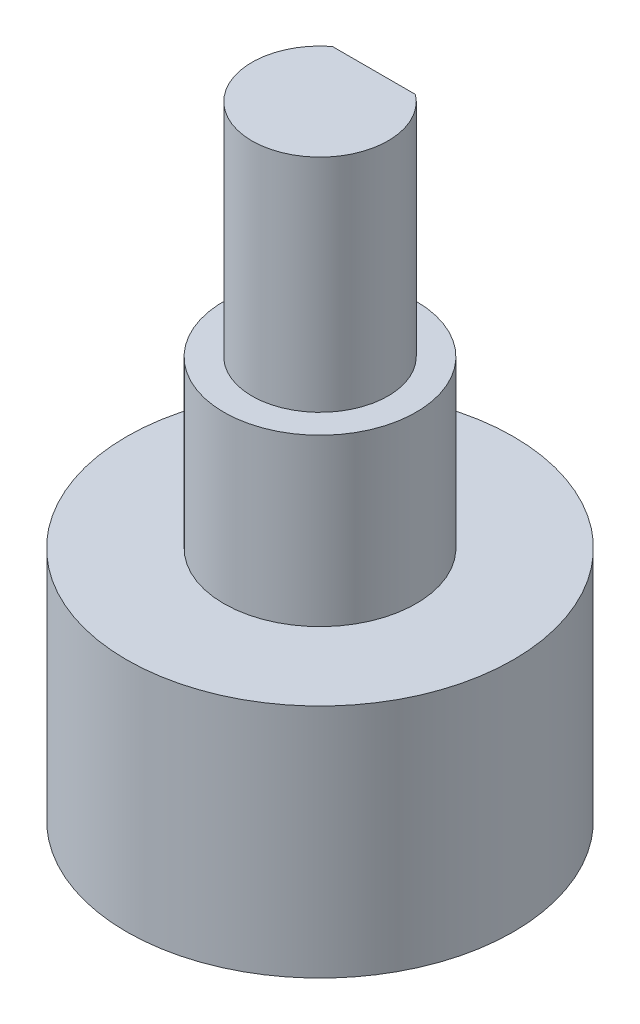
SolidWorks part; units mm, degrees
ref_plane "Front Plane" through (0, 0, 0) normal (0, 0, 1) x (1, 0, 0)
ref_plane "Top Plane" through (0, 0, 0) normal (0, 1, 0) x (1, 0, 0)
ref_plane "Right Plane" through (0, 0, 0) normal (1, 0, 0) x (0, 0, -1)
sketch "Sketch1" plane through (0, 0, 0) normal (0, 1, 0) x (1, 0, 0)
  circle A0 centre (0, 0) radius 11.1125
  dimension "D1" = 22.225
extrude "Boss-Extrude1" add sketch "Sketch1" along normal blind 13.54
sketch "Sketch2" plane through (0, 13.54, 0) normal (0, 1, 0) x (1, 0, 0)
  circle A0 centre (0, 0) radius 5.5245
  dimension "D1" = 11.049
extrude "Boss-Extrude2" add sketch "Sketch2" along normal blind 9.525
sketch "Sketch3" plane through (0, 23.065, 0) normal (0, 1, 0) x (1, 0, 0)
  line L0 (0, 0) -> (0, 3.9116) construction
  line L1 (2.3871, 3.0988) -> (-2.3871, 3.0988)
  arc A0 (-2.3871, 3.0988) -> (2.3871, 3.0988) centre (0, 0) ccw
  point P7 (0, 3.0988)
  dimension "D1" = 7.8232
  dimension "D2" = 0.8128
  dimension "D3" = 3.9116
extrude "Boss-Extrude3" add sketch "Sketch3" along normal blind 12.7
